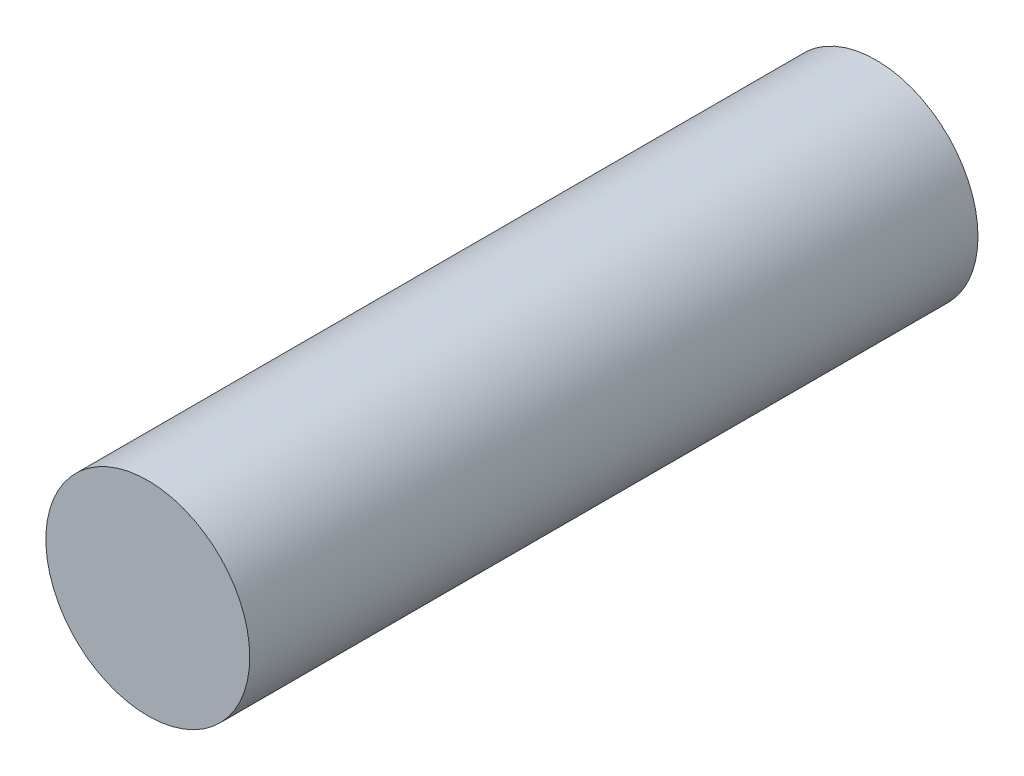
SolidWorks part; units mm, degrees
ref_plane "Front Plane" through (0, 0, 0) normal (0, 0, 1) x (1, 0, 0)
ref_plane "Top Plane" through (0, 0, 0) normal (0, 1, 0) x (1, 0, 0)
ref_plane "Right Plane" through (0, 0, 0) normal (1, 0, 0) x (0, 0, -1)
other "Configuration Table"
sketch "Sketch1" plane through (0, 0, 0) normal (0, 0, 1) x (1, 0, 0)
  circle A0 centre (655, 14) radius 14
extrude "FKAP_mentese_motoru_D28" add sketch "Sketch1" against normal blind 100 from offset 40 separate body
